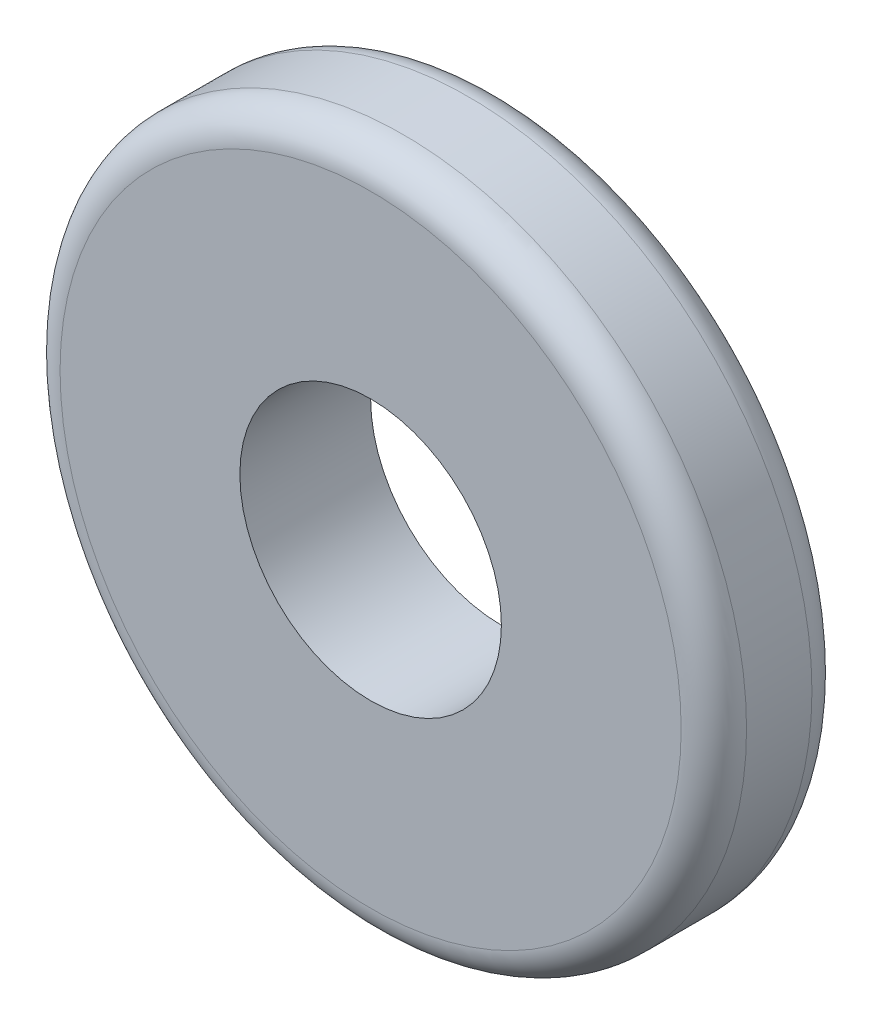
SolidWorks part; units mm, degrees
material "普通碳钢"
ref_plane "前视基准面" through (0, 0, 0) normal (0, 0, 1) x (1, 0, 0)
ref_plane "上视基准面" through (0, 0, 0) normal (0, 1, 0) x (1, 0, 0)
ref_plane "右视基准面" through (0, 0, 0) normal (1, 0, 0) x (0, 0, -1)
sketch "草图1" plane through (0, 0, 0) normal (0, 0, 1) x (1, 0, 0)
  circle A0 centre (0, 0) radius 10.5
  circle A1 centre (0, 0) radius 4
  dimension "D1" = 21
  dimension "D2" = 8
extrude "凸台-拉伸1" add sketch "草图1" along normal blind 4
fillet "圆角1" radius 1 2 edges at (10.5, 0, 0) (10.5, 0, 4)
